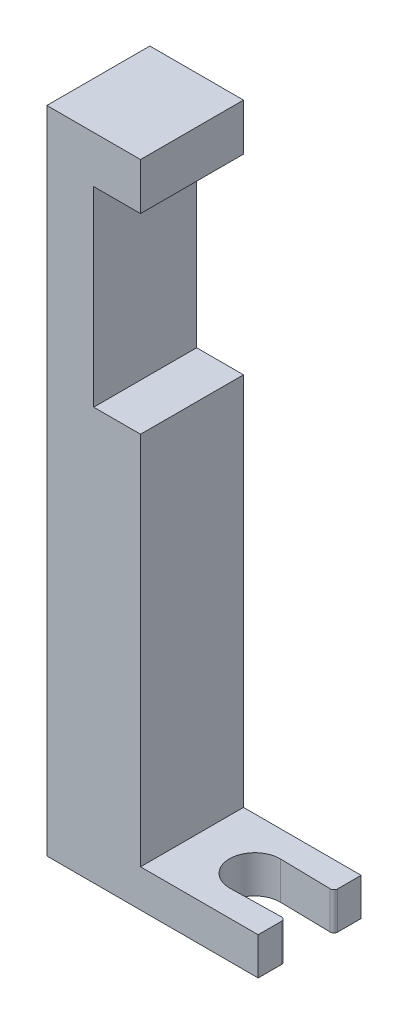
SolidWorks part; units mm, degrees
ref_plane "Front Plane" through (0, 0, 0) normal (0, 0, 1) x (1, 0, 0)
ref_plane "Top Plane" through (0, 0, 0) normal (0, 1, 0) x (1, 0, 0)
ref_plane "Right Plane" through (0, 0, 0) normal (1, 0, 0) x (0, 0, -1)
sketch "Sketch1" plane through (0, 0, 0) normal (0, 1, 0) x (1, 0, 0)
  line L0 (-5.6242, 11.6727) -> (-19.9492, 11.6727)
  line L1 (-19.9492, 11.6727) -> (-19.9492, 18.6529)
  line L2 (-19.9492, 18.6529) -> (-5.6242, 18.6529)
  line L3 (-5.6242, 18.6529) -> (-5.6242, 17.0654)
  line L4 (-5.8831, 16.8114) -> (-9.3114, 16.8773)
  line L5 (-9.3114, 13.4483) -> (-5.8831, 13.5142)
  line L6 (-5.6242, 13.2602) -> (-5.6242, 11.6727)
  line L7 (-11.0592, 15.1628) -> (-11.0592, 18.6529) construction
  line L8 (-9.3114, 13.4483) -> (-9.3114, 16.8773) construction
  arc A0 (-5.8831, 13.5142) -> (-5.6242, 13.2602) centre (-5.8782, 13.2602) cw
  arc A1 (-5.6242, 17.0654) -> (-5.8831, 16.8114) centre (-5.8782, 17.0654) cw
  arc A2 (-9.3114, 16.8773) -> (-9.3114, 13.4483) centre (-9.3444, 15.1628) ccw
  dimension "D2" = 0.254
  dimension "D5" = 8.89
  dimension "D1" = 3.429
  dimension "D4" = 1.5875
extrude "ScrewHook" add sketch "Sketch1" along normal blind 2.54
sketch "Sketch3" plane through (0, 0, -11.6727) normal (0, 0, 1) x (1, 0, 0)
  line L0 (-19.9492, 2.54) -> (-19.9492, 44.069)
  line L1 (-19.9492, 44.069) -> (-13.5992, 44.069)
  line L2 (-13.5992, 44.069) -> (-13.5992, 40.894)
  line L3 (-13.5992, 40.894) -> (-16.7742, 40.894)
  line L4 (-16.7742, 40.894) -> (-16.7742, 27.94)
  line L5 (-16.7742, 27.94) -> (-13.5992, 27.94)
  line L6 (-13.5992, 27.94) -> (-13.5992, 2.54)
  line L7 (-19.9492, 2.54) -> (-5.6242, 2.54) construction
  line L8 (-13.5992, 2.54) -> (-19.9492, 2.54)
  dimension "D1" = 12.954
  dimension "D2" = 3.175
  dimension "D3" = 3.175
  dimension "D4" = 3.175
  dimension "D5" = 25.4
extrude "SpacerAndTopHook" add sketch "Sketch3" against normal up to surface (6.9801 mm away) up to face at (-12.7867, 1.27, -18.6529)
equation "\"BladderHolderThickness\"=0.51"
equation "\"D1@Sketch3\"=\"BladderHolderThickness\""
